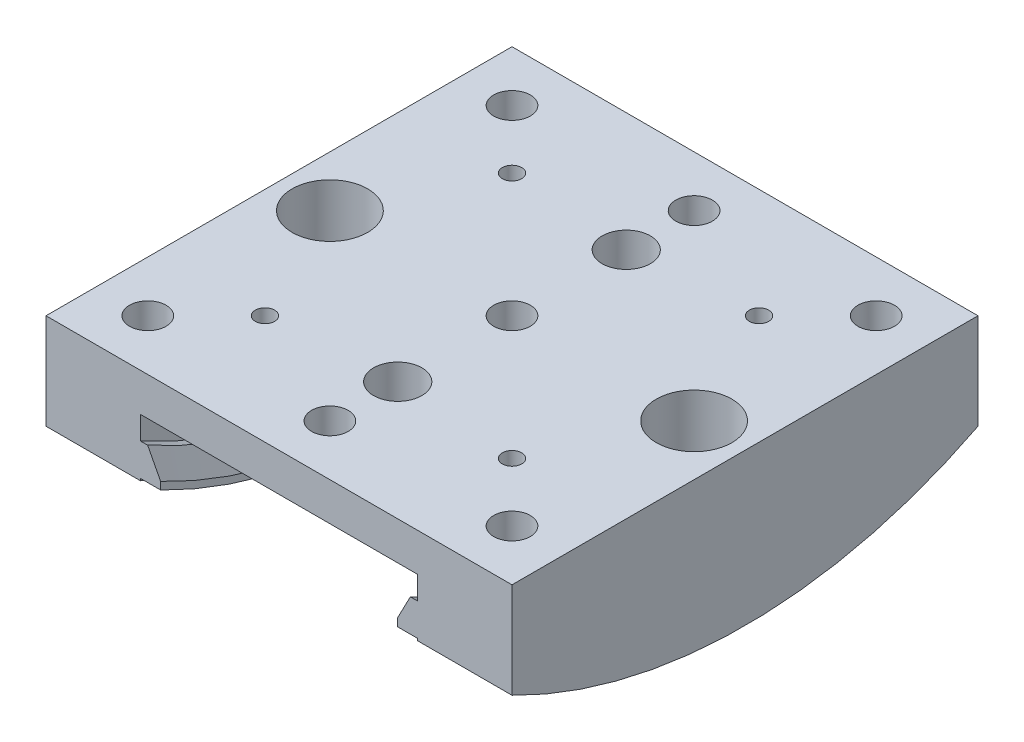
SolidWorks part; units mm, degrees
ref_plane "Ebene vorne" through (0, 0, 0) normal (0, 0, 1) x (1, 0, 0)
ref_plane "Ebene oben" through (0, 0, 0) normal (0, 1, 0) x (1, 0, 0)
ref_plane "Ebene rechts" through (0, 0, 0) normal (1, 0, 0) x (0, 0, -1)
sketch "Skizze1" plane through (0, 0, 0) normal (0, 0, 1) x (1, 0, 0)
  line L1 (-32.5, 15) -> (32.5, 15)
  line L2 (-32.5, 15) -> (-32.5, -15)
  line L3 (-32.5, -15) -> (32.5, -15)
  line L4 (32.5, 15) -> (32.5, -15)
  point P4 (0, 15)
  point P6 (-32.5, 0)
  dimension "D1" = 30
  dimension "D2" = 65
extrude "Aufsatz-Linear austragen1" add sketch "Skizze1" along normal blind 65
sketch "Skizze7" plane through (0, 0, 65) normal (0, 0, 1) x (1, 0, 0)
  line L0 (19.3299, 9.6751) -> (-19.3299, 9.6751)
  line L1 (-19.3299, 9.6751) -> (-19.3299, 6.4564)
  line L2 (-19.3299, 6.4564) -> (-18.3209, 6.4564)
  line L3 (-18.3209, 6.4564) -> (-16.5088, 2.9847)
  line L4 (-16.5088, 2.9847) -> (-16.5088, 1.9417)
  line L5 (-16.5088, 1.9417) -> (-19.3299, 1.9417)
  line L6 (-19.3299, 1.9417) -> (-19.3299, 1.6517)
  line L7 (-19.3299, 1.6517) -> (19.3299, 1.6517)
  line L9 (32.5, 15) -> (-32.5, 15) construction
  line L11 (19.3298, 1.9417) -> (19.3299, 1.6517)
  line L12 (16.5088, 1.9417) -> (19.3298, 1.9417)
  line L13 (16.5088, 2.9847) -> (16.5088, 1.9417)
  line L14 (18.3209, 6.4564) -> (16.5088, 2.9847)
  line L15 (19.3299, 6.4564) -> (18.3209, 6.4564)
  line L16 (19.3299, 9.6751) -> (19.3299, 6.4564)
  point P0 (0, 9.6751)
  point P9 (0, 15)
  dimension "D1" = 3.2187
  dimension "D2" = 1.009
  dimension "D3" = 1.043
  dimension "D4" = 38.6597
  dimension "D5" = 5.3249
  dimension "D6" = 2.821
  dimension "D7" = 0.29
  dimension "D8" = 13.3483
sketch "Skizze8" plane through (0, 0, 0) normal (1, 0, 0) x (0, 0, -1)
  line L0 (-65, 15) -> (0, 15) construction
  circle A0 centre (-32.5, 65) radius 71.1987
  point P4 (-32.5, 15)
  dimension "D1" = 142.3974
  dimension "D2" = 50
sweep "Schnitt-Austragung2" cut profiles "Skizze7" path "Skizze8"
sketch "Skizze9" plane through (-32.5, 0, 0) normal (-1, 0, 0) x (0, 0, 1)
  line L0 (65, 15) -> (0, 15) construction
  line L3 (0, 15) -> (0, -15) construction
  line L5 (0, 15) -> (65, 15)
  line L6 (0, 15) -> (0, -15)
  line L7 (0, -15) -> (65, -15)
  line L8 (65, 15) -> (65, -15)
  circle A0 centre (32.5, 65) radius 71.1987
  point P4 (32.5, 15)
  line M3 (0, -15) -> (65, -15)
  line M4 (65, -15) -> (65, 15)
  dimension "D1" = 142.3974
  dimension "D2" = 50
extrude "Schnitt-Linear austragen2" cut sketch "Skizze9" against normal through all both and the other way through all contours A0 L6 M3 M4
sketch "Skizze10" plane through (0, 15, 0) normal (0, 1, 0) x (1, 0, 0)
  line L0 (-32.5, -65) -> (-32.5, 0) construction
  line L1 (0, -16.5) -> (0, 16.5) construction
  line L2 (-25.399, -32.5) -> (25.399, -32.5) construction
  line L3 (32.5, 0) -> (-32.5, 0) construction
  line L4 (0, -16.562) -> (0, -48.438) construction
  circle A0 centre (-25.399, -32.5) radius 5.2705
  circle A1 centre (25.399, -32.5) radius 5.2705
  circle A2 centre (0, -16.562) radius 3.3655
  circle A3 centre (0, -48.438) radius 3.3655
  circle A4 centre (-25.4, -7.1) radius 2.5525
  circle A6 centre (25.4, -7.1) radius 2.5525
  circle A10 centre (0, -7.1) radius 2.5525
  circle A11 centre (25.4, -57.9) radius 2.5525
  circle A12 centre (0, -57.9) radius 2.5525
  circle A13 centre (-25.4, -57.9) radius 2.5525
  circle A14 centre (-17.227, -15.273) radius 1.3525
  circle A15 centre (17.227, -15.273) radius 1.3525
  circle A16 centre (17.227, -49.727) radius 1.3525
  circle A17 centre (-17.227, -49.727) radius 1.3525
  circle A18 centre (0, -32.5) radius 2.5525
  point P4 (-32.5, -32.5)
  dimension "D1" = 10.541
  dimension "D3" = 6.731
  dimension "D5" = 5.105
  dimension "D8" = 2.705
  dimension "D11" = 5.105
  dimension "D2" = 7.101
  dimension "D4" = 16.562
  dimension "D6" = 7.1
  dimension "D7" = 7.1
  dimension "D9" = 15.273
  dimension "D10" = 15.273
extrude "Schnitt-Linear austragen4" cut sketch "Skizze10" against normal up to next
